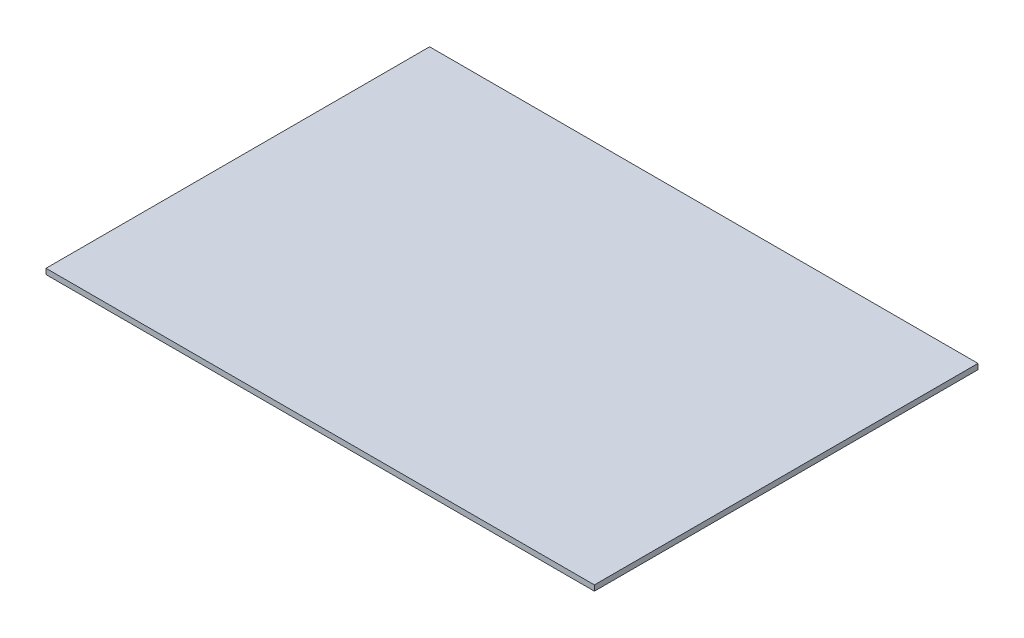
SolidWorks part; units mm, degrees
material "Acrílico (Impacto medio-alto)"
ref_plane "Front" through (0, 0, 0) normal (0, 0, 1) x (1, 0, 0)
ref_plane "Top" through (0, 0, 0) normal (0, 1, 0) x (1, 0, 0)
ref_plane "Right" through (0, 0, 0) normal (1, 0, 0) x (0, 0, -1)
sketch "Croquis1" plane through (0, 0, 0) normal (0, 1, 0) x (1, 0, 0)
  line L0 (-1000, 349.2) -> (1000, 349.2)
  line L1 (-1000, -400) -> (1000, -400) construction
  line L2 (-1000, -400) -> (-1000, 400) construction
  line L3 (-1000, 400) -> (1000, 400) construction
  line L4 (1000, -400) -> (1000, 400) construction
  line L5 (-1000, -400) -> (1000, 400) construction
  line L6 (-1000, 400) -> (1000, -400) construction
  line L7 (-1000, -349.2) -> (1000, -349.2)
  line L8 (-1000, 349.2) -> (-1000, 400)
  line L9 (-1000, 400) -> (1000, 400)
  line L10 (1000, 400) -> (1000, 349.2)
  line L11 (-1000, -349.2) -> (-1000, -400)
  line L12 (-1000, -400) -> (1000, -400)
  line L13 (1000, -400) -> (1000, -349.2)
  line L14 (-499.2, 400) -> (-499.2, -400)
  line L15 (-448.4, 400) -> (-448.4, -400)
  line L16 (550, 400) -> (550, -400)
  line L17 (600.8, 400) -> (600.8, -400)
  line L18 (0, -349.2) -> (0, 349.2)
  line L19 (-499.2, -400) -> (-599.2, -400)
  line L20 (-499.2, -400) -> (-499.2, -450.8)
  line L21 (-499.2, -450.8) -> (-599.2, -450.8)
  line L22 (-599.2, -400) -> (-599.2, -450.8)
  line L23 (-499.2, 400) -> (-599.2, 400)
  line L24 (-499.2, 400) -> (-499.2, 404.709)
  line L25 (-499.2, 404.709) -> (-599.2, 404.709)
  line L26 (-599.2, 400) -> (-599.2, 404.709)
  line L27 (550, -40) -> (550, 40)
  line L28 (550, 40) -> (600.8, 40)
  line L29 (550, 40) -> (550, -40)
  line L30 (550, -40) -> (600.8, -40)
  line L31 (600.8, 40) -> (600.8, -40)
  line L32 (0, 0) -> (550, 0) construction
  line L33 (550, 200) -> (550, -200)
  line L34 (550, -200) -> (600.8, -200)
  line L35 (600.8, -200) -> (600.8, 200)
  line L36 (600.8, 200) -> (550, 200)
  point P0 (0, 0)
  point P35 (0, 0)
  dimension "D1" = 50.8
  dimension "D2" = 50.8
  dimension "D3" = 800
  dimension "D4" = 2000
  dimension "D5" = 50.8
  dimension "D6" = 50.8
  dimension "D7" = 1100
  dimension "D8" = 550
  dimension "D9" = 50.8
  dimension "D10" = 100
  dimension "D11" = 100
  dimension "D12" = 80
  dimension "D13" = 400
  dimension "D14" = 160
extrude "Saliente-Extruir1" add sketch "Croquis1" along normal blind 10 contours L7 L18 L0 L15 | L18 L7 L16 L0
